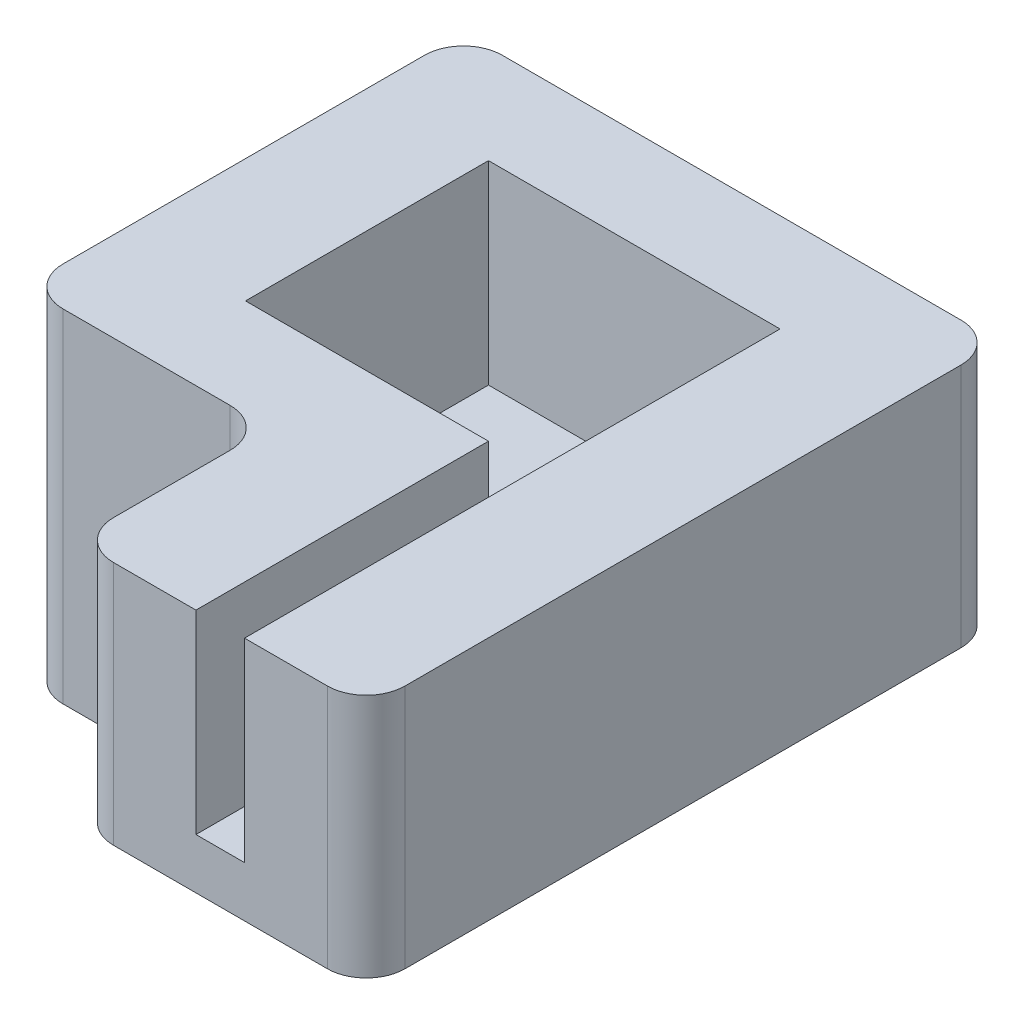
SolidWorks part; units mm, degrees
ref_plane "Front Plane" through (0, 0, 0) normal (0, 0, 1) x (1, 0, 0)
ref_plane "Top Plane" through (0, 0, 0) normal (0, 1, 0) x (1, 0, 0)
ref_plane "Right Plane" through (0, 0, 0) normal (1, 0, 0) x (0, 0, -1)
sketch "Sketch1" plane through (0, 0, 0) normal (0, 1, 0) x (1, 0, 0)
  line L1 (-17.526, 14.351) -> (17.526, 14.351)
  line L2 (-17.526, 14.351) -> (-17.526, -14.351)
  line L3 (-17.526, -14.351) -> (17.526, -14.351)
  line L4 (17.526, 14.351) -> (17.526, -14.351)
  line L5 (-17.526, 14.351) -> (17.526, -14.351) construction
  line L6 (-17.526, -14.351) -> (17.526, 14.351) construction
  point P0 (0, 0)
  dimension "D1" = 35.052
  dimension "D2" = 28.702
extrude "Boss-Extrude5" add sketch "Sketch1" along normal blind 22.352
sketch "Sketch6" plane through (17.526, 0, 0) normal (1, 0, 0) x (0, 0, -1)
  line L0 (14.351, 0) -> (14.351, 6.35)
  line L1 (14.351, 0) -> (-14.351, 0)
  line L2 (14.351, 6.35) -> (-14.351, 6.35)
  line L3 (-14.351, 0) -> (-14.351, 6.35)
  line L4 (14.351, 22.352) -> (14.351, 0) construction
  line L5 (-14.351, 0) -> (14.351, 0) construction
  dimension "D1" = 6.35
extrude "Cut-Extrude1" cut sketch "Sketch6" against normal blind 6.35
sketch "Sketch7" plane through (0, 0, 14.351) normal (0, 0, 1) x (1, 0, 0)
  line L0 (17.526, 22.352) -> (17.526, 6.35)
  line L1 (17.526, 22.352) -> (-1.524, 22.352)
  line L2 (17.526, 6.35) -> (-1.524, 6.35)
  line L3 (-1.524, 22.352) -> (-1.524, 6.35)
  dimension "D1" = 19.05
extrude "Boss-Extrude6" add sketch "Sketch7" along normal blind 12.7
sketch "Sketch8" plane through (0, 22.352, 0) normal (0, 1, 0) x (1, 0, 0)
  line L0 (-9.4742, 7.9375) -> (-9.4742, -7.9375)
  line L1 (-9.4742, -7.9375) -> (6.4008, -7.9375)
  line L2 (6.4008, -7.9375) -> (6.4008, -27.051)
  line L3 (17.526, -27.051) -> (-1.524, -27.051) construction
  line L4 (6.4008, -27.051) -> (9.5758, -27.051)
  line L5 (9.5758, -27.051) -> (9.5758, 7.9375)
  line L6 (9.5758, 7.9375) -> (-9.4742, 7.9375)
  line L8 (-17.526, -14.351) -> (-1.524, -14.351) construction
  line L11 (17.526, -27.051) -> (17.526, 14.351) construction
  dimension "D1" = 15.875
  dimension "D2" = 19.05
  dimension "D3" = 3.175
  dimension "D4" = 6.4135
  dimension "D5" = 7.9502
extrude "Cut-Extrude2" cut sketch "Sketch8" against normal blind 12.7
fillet "Fillet5" radius 2.54 5 edges at (17.526, 14.351, -14.351) (11.176, 3.175, -14.351) (-17.526, 11.176, -14.351) (-17.526, 11.176, 14.351) (-1.524, 14.351, 14.351)
fillet "Fillet6" radius 2.54 3 edges at (-1.524, 14.351, 27.051) (11.176, 3.175, 14.351) (17.526, 14.351, 27.051)
